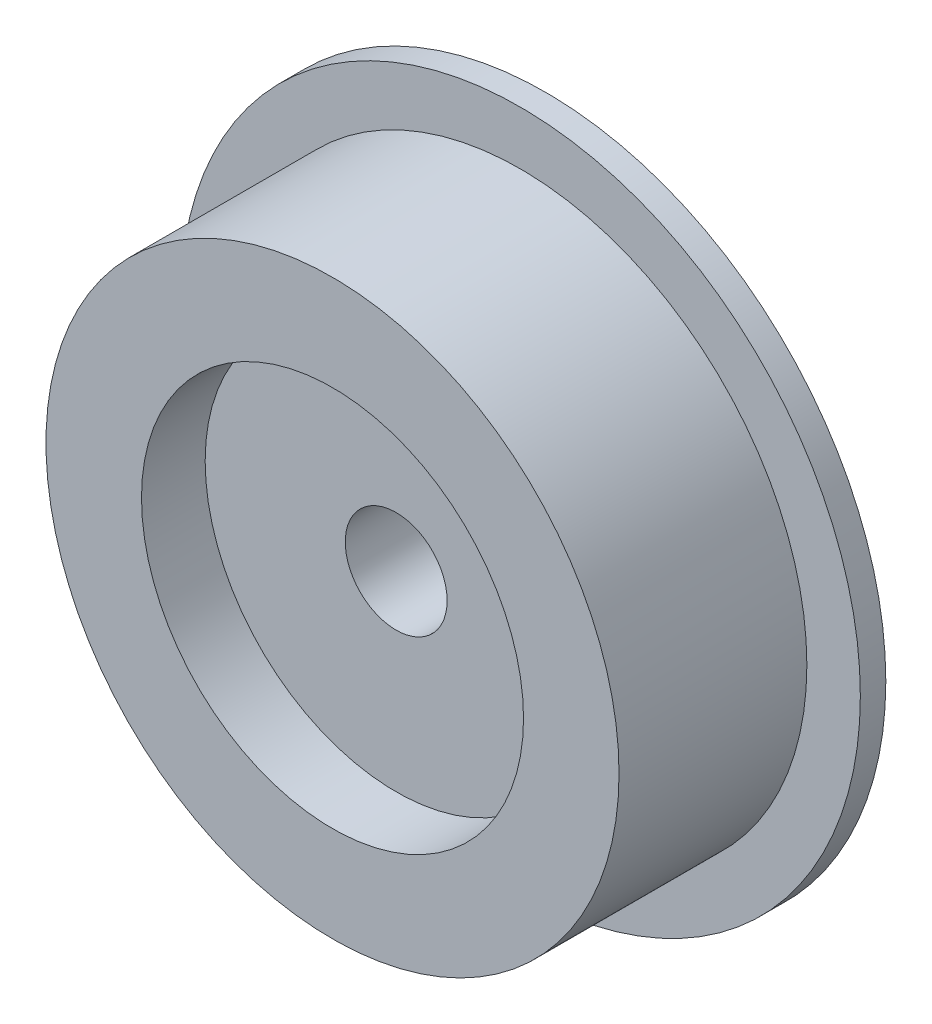
SolidWorks part; units mm, degrees
ref_plane "Front Plane" through (0, 0, 0) normal (0, 0, 1) x (1, 0, 0)
ref_plane "Top Plane" through (0, 0, 0) normal (0, 1, 0) x (1, 0, 0)
ref_plane "Right Plane" through (0, 0, 0) normal (1, 0, 0) x (0, 0, -1)
sketch "Sketch3" plane through (0, 0, 0) normal (0, 0, 1) x (1, 0, 0)
  circle A0 centre (0, 0) radius 53.4
  dimension "D1" = 106.8
extrude "Boss-Extrude1" add sketch "Sketch3" against normal blind 38.5
sketch "Sketch4" plane through (0, 0, 0) normal (0, 0, 1) x (1, 0, 0)
  circle A0 centre (0, 0) radius 8
  dimension "D1" = 16
extrude "Cut-Extrude1" cut sketch "Sketch4" against normal through all
sketch "Sketch5" plane through (0, 0, 0) normal (0, 0, 1) x (1, 0, 0)
  line L0 (0, 0) -> (-17.6777, 17.6777) construction
  line L1 (0, 0) -> (0, 25) construction
  line L2 (0, 0) -> (17.6777, -17.6777) construction
  line L3 (0, 0) -> (17.6777, 17.6777) construction
  line L4 (0, 0) -> (-17.6777, -17.6777) construction
  arc A0 (-19.0342, -16.208) -> (-16.208, -19.0342) centre (0, 0) ccw
  circle A1 centre (-17.6777, 17.6777) radius 2
  circle A2 centre (17.6777, 17.6777) radius 2
  circle A3 centre (-17.6777, -17.6777) radius 2
  circle A4 centre (17.6777, -17.6777) radius 2
  dimension "D1" = 50
  dimension "D4" = 4
  dimension "D5" = 4
  dimension "D6" = 4
  dimension "D7" = 4
  dimension "D2" = 45
  dimension "D3" = 45
sketch "Sketch6" plane through (0, 0, 0) normal (0, 0, 1) x (1, 0, 0)
  circle A0 centre (0, 0) radius 16
  circle A1 centre (0, 0) radius 8
  dimension "D1" = 32
  dimension "D2" = 16
extrude "Boss-Extrude3" add sketch "Sketch6" along normal blind 2
sketch "Sketch7" plane through (0, 0, 0) normal (0, 0, 1) x (1, 0, 0)
  line L0 (0, 0) -> (20, 0) construction
  line L1 (0, 0) -> (0, 20) construction
  arc A0 (-19.8898, 2.0971) -> (-19.8898, -2.0971) centre (0, 0) ccw
  circle A1 centre (0, 20) radius 2.1
  circle A2 centre (20, 0) radius 2.1
  circle A3 centre (-20, 0) radius 2.1
  circle A4 centre (0, -20) radius 2.1
  arc A5 (-2.0971, -19.8898) -> (2.0971, -19.8898) centre (0, 0) ccw
  arc A6 (19.8898, -2.0971) -> (19.8898, 2.0971) centre (0, 0) ccw
  arc A7 (2.0971, 19.8898) -> (-2.0971, 19.8898) centre (0, 0) ccw
  dimension "D1" = 40
  dimension "D2" = 4.2
  dimension "D3" = 4.2
  dimension "D4" = 4.2
  dimension "D5" = 4.2
sketch "Sketch8" plane through (0, 0, -38.5) normal (0, 0, -1) x (-1, 0, 0)
  line L0 (0, 27.5) -> (0, 30) construction
  line L1 (0, 0) -> (0, -30) construction
  line L2 (27.5, 0) -> (30, 0) construction
  line L3 (0, 0) -> (-30, 0) construction
  arc A0 (-29.8958, 2.4978) -> (-29.8958, -2.4978) centre (0, 0) ccw
  circle A1 centre (0, 30) radius 2.5
  circle A2 centre (30, 0) radius 2.5
  circle A3 centre (0, -30) radius 2.5
  circle A4 centre (-30, 0) radius 2.5
  arc A5 (2.4978, 29.8958) -> (-2.4978, 29.8958) centre (0, 0) ccw
  arc A6 (29.8958, -2.4978) -> (29.8958, 2.4978) centre (0, 0) ccw
  arc A7 (-2.4978, -29.8958) -> (2.4978, -29.8958) centre (0, 0) ccw
  dimension "D1" = 60
  dimension "D2" = 5
  dimension "D3" = 5
  dimension "D4" = 5
  dimension "D5" = 5
extrude "Cut-Extrude4" cut sketch "Sketch8" against normal blind 20 contours A4 | A1 | A2 | A3
sketch "Sketch9" plane through (0, 0, 0) normal (0, 0, 1) x (1, 0, 0)
  circle A0 centre (0, 0) radius 53.4 construction
  circle A1 centre (0, 0) radius 53.4
  circle A2 centre (0, 0) radius 45
  dimension "D1" = 90
extrude "Cut-Extrude5" cut sketch "Sketch9" against normal blind 34.5 contours A2 | A1
sketch "Sketch10" plane through (0, 0, 0) normal (0, 0, 1) x (1, 0, 0)
  circle A0 centre (0, 0) radius 50
  dimension "D1" = 100
extrude "Cut-Extrude6" cut sketch "Sketch10" against normal blind 5 and the other way blind 2 contours A0
sketch "Sketch11" plane through (0, 0, -5) normal (0, 0, 1) x (1, 0, 0)
  circle A0 centre (0, 0) radius 30
  dimension "D1" = 60
extrude "Cut-Extrude7" cut sketch "Sketch11" against normal blind 10
